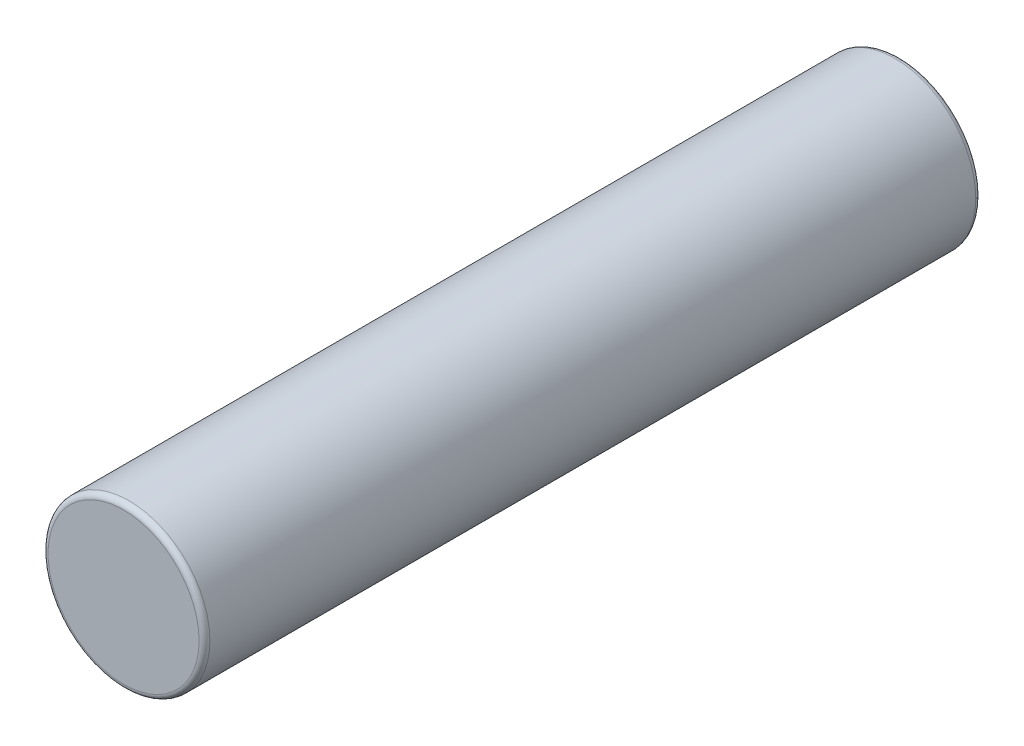
SolidWorks part; units mm, degrees
ref_plane "前基準面" through (0, 0, 0) normal (0, 0, 1) x (1, 0, 0)
ref_plane "上基準面" through (0, 0, 0) normal (0, 1, 0) x (1, 0, 0)
ref_plane "右基準面" through (0, 0, 0) normal (1, 0, 0) x (0, 0, -1)
sketch "草圖1" plane through (0, 0, 0) normal (0, 0, 1) x (1, 0, 0)
  circle A0 centre (0, 0) radius 0.75
  dimension "D1" = 1.5
extrude "伸長1" add sketch "草圖1" along normal blind 7.2
fillet "圓角1" radius 0.05 2 edges at (0.75, 0, 0) (0.75, 0, 7.2)
